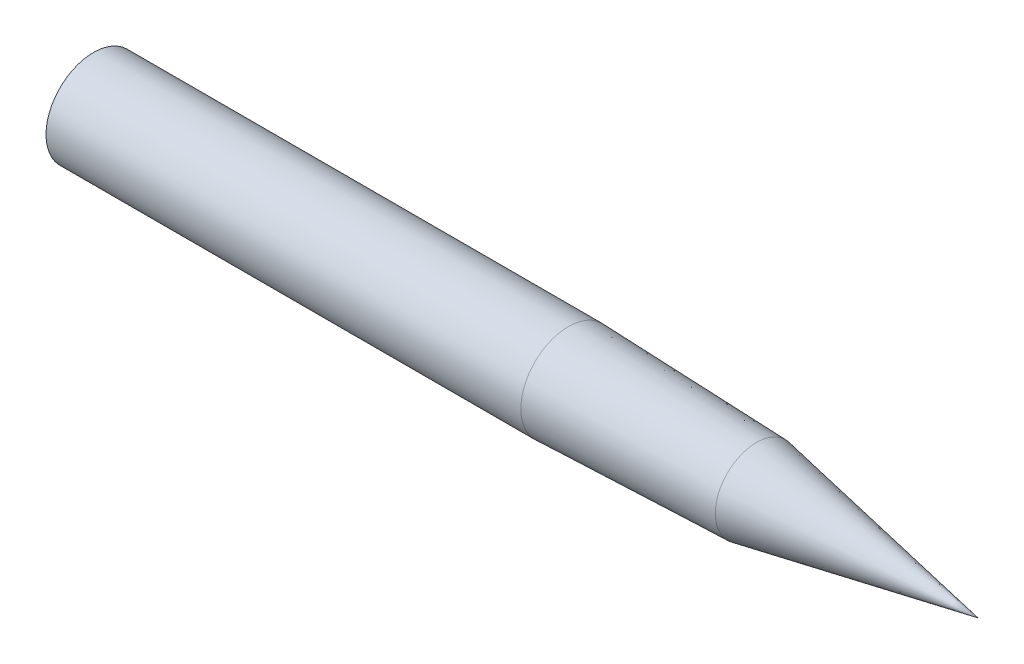
SolidWorks part; units mm, degrees
ref_plane "Front Plane" through (0, 0, 0) normal (0, 0, 1) x (1, 0, 0)
ref_plane "Top Plane" through (0, 0, 0) normal (0, 1, 0) x (1, 0, 0)
ref_plane "Right Plane" through (0, 0, 0) normal (1, 0, 0) x (0, 0, -1)
sketch "Sketch1" plane through (0, 0, 0) normal (0, 0, 1) x (1, 0, 0)
  line L0 (0, 0) -> (27.9391, 0)
  line L2 (0, 1.5) -> (0, 0)
  line L10 (0, 1.5) -> (15, 1.5)
  line L11 (15, 1.5) -> (20.9391, 1.3)
  line L12 (20.9391, 1.3) -> (27.9391, 0)
  point P1 (0, 1.5)
  point P3 (29.7447, 0.0366)
  point P5 (0.0562, 1.5)
  dimension "D2" = 1.3
  dimension "D3" = 1.5
  dimension "D5" = 1.5
  dimension "D6" = 15
  dimension "D7" = 7
revolve "Revolve1" add sketch "Sketch1" angle 360 about L0
